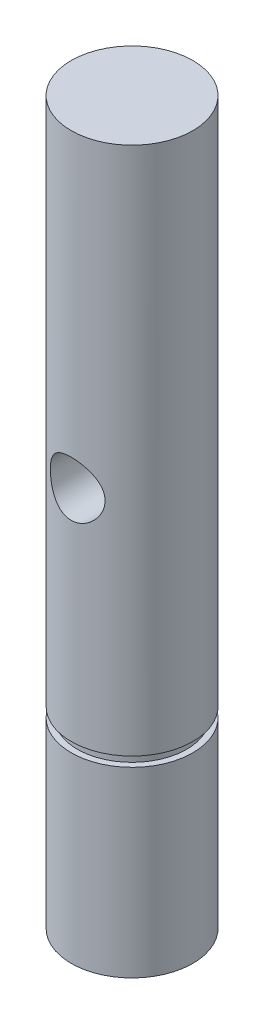
SolidWorks part; units mm, degrees
ref_plane "Front Plane" through (0, 0, 0) normal (0, 0, 1) x (1, 0, 0)
ref_plane "Top Plane" through (0, 0, 0) normal (0, 1, 0) x (1, 0, 0)
ref_plane "Right Plane" through (0, 0, 0) normal (1, 0, 0) x (0, 0, -1)
sketch "Sketch1" plane through (0, 0, 0) normal (0, 1, 0) x (1, 0, 0)
  circle A0 centre (0, 0) radius 5
  dimension "D1" = 10
extrude "Boss-Extrude1" add sketch "Sketch1" along normal blind 59.3
sketch "Sketch2" plane through (0, 0, 0) normal (0, -1, 0) x (1, 0, 0)
  circle A0 centre (0, 0) radius 4.5
  circle M1 centre (0, 0) radius 5
  dimension "D1" = 9
extrude "Cut-Extrude1" cut sketch "Sketch2" against normal blind 0.8 from offset 15 contours A0 M1 offset against normal yes
ref_plane "Plane1" through (0, 0, 5) normal (0, 0, 1) x (1, 0, 0)
sketch "Sketch3" plane through (0, 0, 5) normal (0, 0, 1) x (1, 0, 0)
  line L0 (5, 59.3) -> (-5, 59.3) construction
  circle A0 centre (0, 33.8) radius 2
  dimension "D2" = 4
  dimension "D1" = 25.5
sketch "Sketch4" plane through (0, 0, 5) normal (0, 0, 1) x (1, 0, 0)
  point P0 (0, 33.8)
hole_wizard "M4 Clearance Hole1" positions "Sketch4" profile "Sketch5" hole size "M4" standard "ANSI Metric" end condition through all
sketch "Sketch5" plane through (0, 33.8, 5) normal (1, 0, 0) x (0, -1, 0)
  line L0 (0, 0) -> (0, 10)
  line L1 (0, 10) -> (2.25, 10)
  line L2 (2.25, 10) -> (2.25, 0)
  line L5 (2.25, 0) -> (0, 0)
  line L11 (0, -6.35) -> (0, 107.95) construction
  dimension "Thru Hole Dia." = 4.5
  dimension "Thru Hole Depth" = 10
